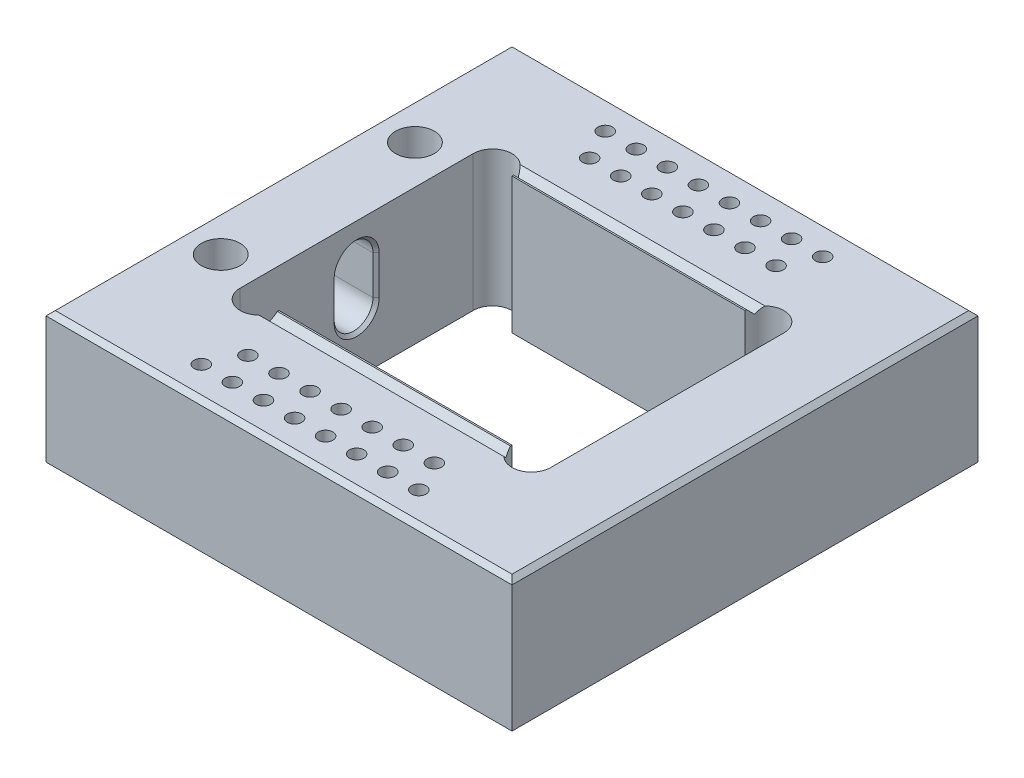
SolidWorks part; units mm, degrees
material "Acrylic (Medium-high impact)"
ref_plane "Front Plane" through (0, 0, 0) normal (0, 0, 1) x (1, 0, 0)
ref_plane "Top Plane" through (0, 0, 0) normal (0, 1, 0) x (1, 0, 0)
ref_plane "Right Plane" through (0, 0, 0) normal (1, 0, 0) x (0, 0, -1)
sketch "Sketch1" plane through (0, 0, 0) normal (0, 1, 0) x (1, 0, 0)
  line L1 (-38.1, 38.1) -> (38.1, 38.1)
  line L2 (-38.1, 38.1) -> (-38.1, -38.1)
  line L3 (-38.1, -38.1) -> (38.1, -38.1)
  line L4 (38.1, 38.1) -> (38.1, -38.1)
  line L5 (-38.1, 38.1) -> (38.1, -38.1) construction
  line L6 (-38.1, -38.1) -> (38.1, 38.1) construction
  point P0 (0, 0)
  dimension "D1" = 76.2
  dimension "D2" = 76.2
extrude "Boss-Extrude1" add sketch "Sketch1" along normal blind 22.225 contours L1 L4 L3 L2
sketch "Sketch2" plane through (0, 22.225, 0) normal (0, 1, 0) x (1, 0, 0)
  line L1 (-22.225, 19.05) -> (22.225, 19.05)
  line L2 (-22.225, 19.05) -> (-22.225, -19.05)
  line L3 (-22.225, -19.05) -> (22.225, -19.05)
  line L4 (22.225, 19.05) -> (22.225, -19.05)
  line L5 (-22.225, 19.05) -> (22.225, -19.05) construction
  line L6 (-22.225, -19.05) -> (22.225, 19.05) construction
  point P0 (0, 0)
  dimension "D1" = 38.1
  dimension "D2" = 44.45
extrude "Cut-Extrude1" cut sketch "Sketch2" against normal through all
sketch "Sketch3" plane through (0, 22.225, 0) normal (0, 1, 0) x (1, 0, 0)
  line L0 (-22.225, 19.05) -> (-22.225, -19.05) construction
  line L1 (-19.05, 19.05) -> (-19.05, -19.05)
  line L2 (-25.4, 19.05) -> (-25.4, -19.05)
  line L3 (22.225, 19.05) -> (22.225, -19.05) construction
  line L4 (25.4, 19.05) -> (25.4, -19.05)
  line L5 (19.05, 19.05) -> (19.05, -19.05)
  arc A0 (-19.05, 19.05) -> (-25.4, 19.05) centre (-22.225, 19.05) ccw
  arc A1 (-25.4, -19.05) -> (-19.05, -19.05) centre (-22.225, -19.05) ccw
  arc A2 (25.4, 19.05) -> (19.05, 19.05) centre (22.225, 19.05) ccw
  arc A3 (19.05, -19.05) -> (25.4, -19.05) centre (22.225, -19.05) ccw
  point P4 (-22.225, 0)
  point P9 (22.225, 0)
  dimension "D1" = 3.175
extrude "Cut-Extrude2" cut sketch "Sketch3" against normal through all
hole_wizard "3/32 (0.09375) Diameter Hole1" positions "Sketch7" profile "Sketch6" hole size "3/32" standard "ANSI Inch" end condition through all
sketch "Sketch7" plane through (0, 22.225, 0) normal (0, 1, 0) x (1, 0, 0)
  line L0 (0, 0) -> (0, 38.1) construction
  line L2 (-15.24, 27.94) -> (15.24, 27.94) construction
  line L3 (-38.1, 38.1) -> (38.1, 38.1) construction
  line L4 (-17.78, 33.02) -> (17.78, 33.02) construction
  point P6 (-15.24, 27.94)
  point P7 (15.24, 27.94)
  point P17 (0, 27.94)
  point P18 (-17.78, 33.02)
  point P19 (17.78, 33.02)
  point P30 (-12.7, 33.02)
  point P31 (-7.62, 33.02)
  point P32 (-2.54, 33.02)
  point P33 (2.54, 33.02)
  point P34 (7.62, 33.02)
  point P35 (12.7, 33.02)
  point P36 (17.78, 33.02)
  point P38 (0, 33.02)
  point P53 (-10.16, 27.94)
  point P54 (-5.08, 27.94)
  point P55 (0, 27.94)
  point P56 (5.08, 27.94)
  point P57 (10.16, 27.94)
  point P58 (15.24, 27.94)
  dimension "D1" = 30.48
  dimension "D2" = 5.08
  dimension "D3" = 27.94
  dimension "D4" = 35.56
  dimension "D5" = 8
  dimension "D6" = 7
sketch "Sketch6" plane through (-15.24, 22.225, -27.94) normal (1, 0, 0) x (0, 0, 1)
  line L0 (0, 0) -> (0, 22.225)
  line L1 (0, 22.225) -> (1.1906, 22.225)
  line L2 (1.1906, 22.225) -> (1.1906, 0)
  line L5 (1.1906, 0) -> (0, 0)
  line L11 (0, -6.35) -> (0, 107.95) construction
  dimension "Thru Hole Dia." = 2.3812
  dimension "Thru Hole Depth" = 22.225
mirror "Mirror1" about plane through (0, 0, 0) normal (0, 0, 1) of "3/32 (0.09375) Diameter Hole1"
sketch "Sketch8" plane through (0, 0, 0) normal (1, 0, 0) x (0, 0, -1)
  line L0 (19.304, 22.225) -> (20.32, 21.209)
  line L1 (-38.1, 22.225) -> (38.1, 22.225) construction
  line L2 (20.32, 21.209) -> (21.336, 22.225)
  line L3 (21.336, 22.225) -> (19.304, 22.225)
  line L4 (20.32, 22.225) -> (20.32, 21.209) construction
  dimension "D1" = 1.016
  dimension "D2" = 20.32
extrude "Cut-Extrude4" cut sketch "Sketch8" against normal mid plane 43.18
mirror "Mirror2" about plane through (0, 0, 0) normal (0, 0, 1) of "Cut-Extrude4"
sketch "Sketch9" plane through (-25.4, 0, 0) normal (1, 0, 0) x (0, 0, -1)
  line L0 (0, 15.875) -> (0, 9.525) construction
  line L1 (3.175, 15.875) -> (3.175, 9.525)
  line L2 (-3.175, 15.875) -> (-3.175, 9.525)
  line L3 (-38.1, 0) -> (38.1, 0) construction
  arc A0 (3.175, 15.875) -> (-3.175, 15.875) centre (0, 15.875) ccw
  arc A1 (-3.175, 9.525) -> (3.175, 9.525) centre (0, 9.525) ccw
  point P3 (0, 12.7)
  dimension "D1" = 6.35
  dimension "D2" = 6.35
  dimension "D3" = 9.525
extrude "Cut-Extrude5" cut sketch "Sketch9" against normal up to next
chamfer "Chamfer1" distance 0.762 angle 45 8 edges at (0, 0, -38.1) (-38.1, 0, 0) (0, 0, 38.1) (38.1, 0, 0) (-38.1, 22.225, 0) (0, 22.225, -38.1) (38.1, 22.225, 0) (0, 22.225, 38.1)
chamfer "Chamfer2" distance 0.508 angle 45 8 edges at (-25.4, 12.7, -3.175) (-25.4, 19.05, 0) (-25.4, 6.35, 0) (-25.4, 12.7, 3.175) (-38.1, 12.7, -3.175) (-38.1, 6.35, 0) (-38.1, 19.05, 0) (-38.1, 12.7, 3.175)
hole_wizard "1/4 (0.25) Diameter Hole1" positions "Sketch10" profile "Sketch11" hole size "1/4" standard "ANSI Inch"
sketch "Sketch10" plane through (0, 22.225, 0) normal (0, 1, 0) x (1, 0, 0)
  line L0 (-31.75, 15.875) -> (-31.75, -15.875) construction
  line L2 (-31.75, 0) -> (0, 0) construction
  line L4 (-38.1, -38.1) -> (-38.1, 38.1) construction
  point P0 (-31.75, 15.875)
  point P2 (-31.75, -15.875)
  dimension "D1" = 31.75
  dimension "D2" = 6.35
sketch "Sketch11" plane through (-31.75, 22.225, -15.875) normal (1, 0, 0) x (0, 0, 1)
  line L0 (0, 0) -> (0, 18.4177)
  line L1 (0, 18.4177) -> (3.175, 16.51)
  line L2 (3.175, 16.51) -> (3.175, 0)
  line L5 (3.175, 0) -> (0, 0)
  line L10 (0, 18.4177) -> (-3.175, 16.51) construction
  line L11 (0, -6.35) -> (0, 107.95) construction
  dimension "Hole Dia." = 6.35
  dimension "Hole Depth" = 16.51
  dimension "Drill Angle" = 118
